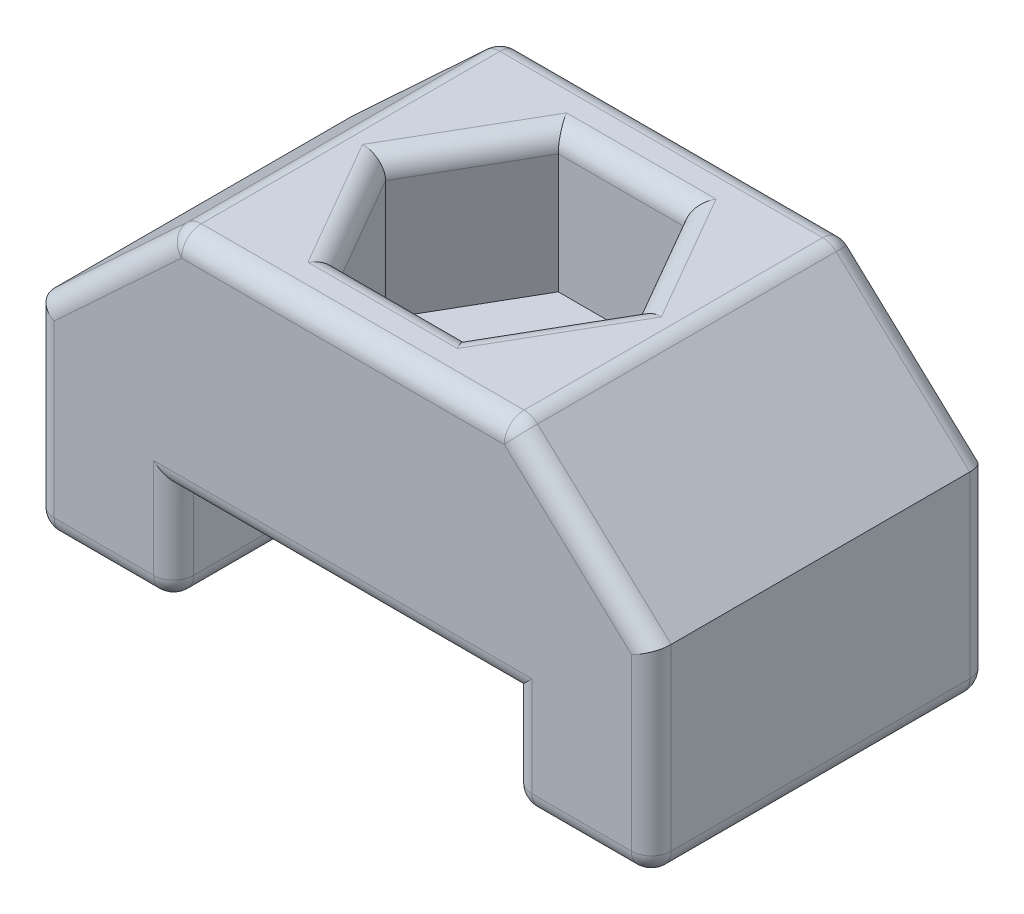
SolidWorks part; units mm, degrees
material "ABS"
ref_plane "Plan de face" through (0, 0, 0) normal (0, 0, 1) x (1, 0, 0)
ref_plane "Plan de dessus" through (0, 0, 0) normal (0, 1, 0) x (1, 0, 0)
ref_plane "Plan de droite" through (0, 0, 0) normal (1, 0, 0) x (0, 0, -1)
sketch "Esquisse1" plane through (0, 0, 0) normal (0, 0, 1) x (1, 0, 0)
  line L0 (0, 0) -> (0, 45.3927) construction
  line L1 (-3, 1.84) -> (3, 1.84)
  line L2 (3, 1.84) -> (8.5, 1.84)
  line L3 (8.5, 1.84) -> (8.5, -3.16)
  line L4 (8.5, -3.16) -> (15.5, -3.16)
  line L5 (15.5, -3.16) -> (15.5, 6.84)
  line L6 (15.5, 6.84) -> (8.5, 13.34)
  line L7 (8.5, 13.34) -> (-8.5, 13.34)
  line L11 (-15.5, 6.84) -> (-8.5, 13.34)
  line L12 (-15.5, -3.16) -> (-15.5, 6.84)
  line L13 (-8.5, -3.16) -> (-15.5, -3.16)
  line L14 (-8.5, 1.84) -> (-8.5, -3.16)
  line L15 (-3, 1.84) -> (-8.5, 1.84)
  dimension "D1" = 6
  dimension "D2" = 5
  dimension "D3" = 5
  dimension "D4" = 7
  dimension "D5" = 11.5
  dimension "D6" = 5.5
  dimension "D7" = 8.5
extrude "Boss.-Extru.1" add sketch "Esquisse1" along normal blind 17
sketch "Esquisse2" plane through (0, 13.34, 0) normal (0, 1, 0) x (1, 0, 0)
  line L0 (-8.5, 0) -> (8.5, -17) construction
  line L2 (6.3509, -8.5) -> (3.1754, -3)
  line L3 (3.1754, -3) -> (-3.1754, -3)
  line L4 (-3.1754, -3) -> (-6.3509, -8.5)
  line L5 (-6.3509, -8.5) -> (-3.1754, -14)
  line L6 (-3.1754, -14) -> (3.1754, -14)
  line L7 (3.1754, -14) -> (6.3509, -8.5)
  circle A0 centre (0, -8.5) radius 5.5 construction
  dimension "D1" = 11
extrude "Enlèv. mat.-Extru.1" cut sketch "Esquisse2" against normal blind 7
sketch "Esquisse3" plane through (0, 6.34, 0) normal (0, 1, 0) x (1, 0, 0)
  line L0 (-8.5, 0) -> (8.5, -17) construction
  circle A0 centre (0, -8.5) radius 3
  point P7 (0, -8.5)
  dimension "D1" = 6
extrude "Enlèv. mat.-Extru.2" cut sketch "Esquisse3" against normal blind 5
fillet "Congé1" radius 1 32 edges at (8.5, 13.34, 8.5) (-8.5, 13.34, 8.5) (0, 13.34, 3) (-4.7631, 13.34, 5.75) (-4.7631, 13.34, 11.25) (0, 13.34, 14) (4.7631, 13.34, 11.25) (4.7631, 13.34, 5.75) (15.5, 1.84, 0) (12, 10.09, 0) (0, 13.34, 0) (-12, 10.09, 0) (-15.5, 1.84, 0) (-8.5, -0.66, 0) (0, 1.84, 0) (8.5, -0.66, 0) (-8.5, -0.66, 17) (-15.5, 1.84, 17) (-12, 10.09, 17) (0, 13.34, 17) (12, 10.09, 17) (15.5, 1.84, 17) (8.5, -0.66, 17) (0, 1.84, 17) (-15.5, -3.16, 8.5) (-12, -3.16, 17) (-8.5, -3.16, 8.5) (-12, -3.16, 0) (8.5, -3.16, 8.5) (12, -3.16, 17) (15.5, -3.16, 8.5) (12, -3.16, 0)
